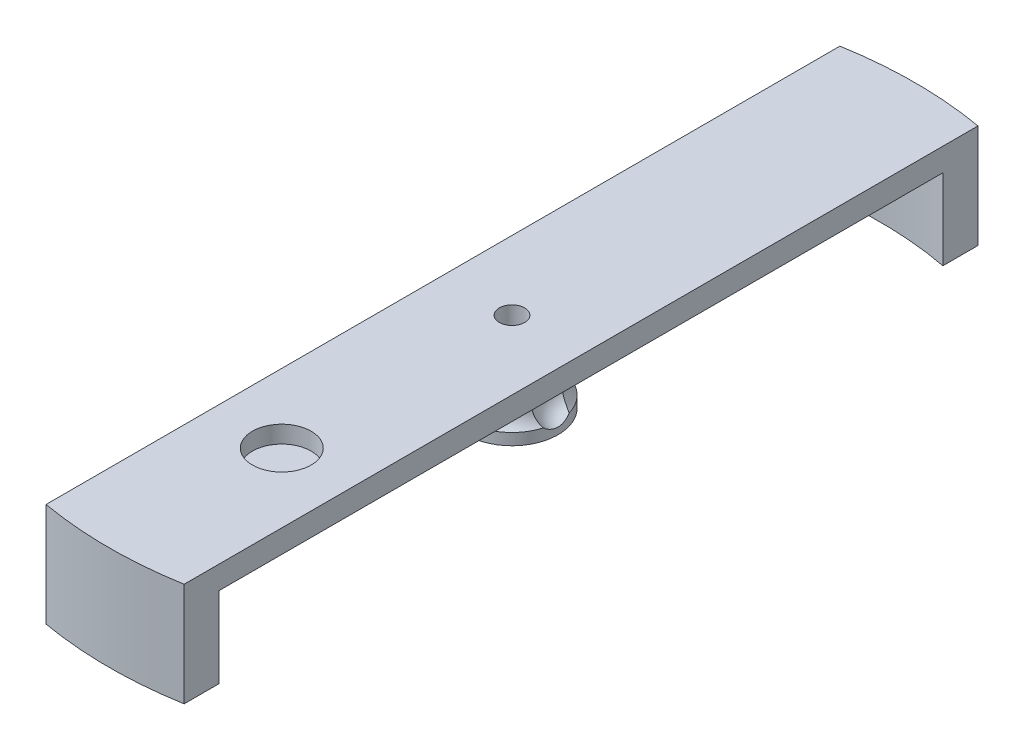
SolidWorks part; units mm, degrees
ref_plane "Plano frontal" through (0, 0, 0) normal (0, 0, 1) x (1, 0, 0)
ref_plane "Plano superior" through (0, 0, 0) normal (0, 1, 0) x (1, 0, 0)
ref_plane "Plano direito" through (0, 0, 0) normal (1, 0, 0) x (0, 0, -1)
sketch "Esboço1" plane through (0, 0, 0) normal (0, 0, 1) x (1, 0, 0)
  line L0 (0, 0) -> (0, 5.1163) construction
  line L1 (1.1, 7) -> (1.1, 0)
  line L6 (3.5, 7) -> (1.1, 7)
  line L7 (1.1, 0) -> (4, 0)
  line L8 (4, 0) -> (4, 1)
  line L9 (4, 4.0397) -> (4, 5)
  line L10 (3.5, 7) -> (35, 7)
  line L11 (35, 7) -> (35, -2)
  line L12 (35, -2) -> (32, -2)
  line L13 (32, -2) -> (32, 5)
  line L14 (32, 5) -> (4, 5)
  arc A1 (4, 4.0397) -> (4, 1) centre (5.3, 2.5199) ccw
  dimension "D3" = 0.7
  dimension "D5" = 2
  dimension "D1" = 2.2
  dimension "D2" = 8
  dimension "D4" = 7
  dimension "D6" = 1
  dimension "D7" = 2
  dimension "D8" = 2
  dimension "D9" = 3
  dimension "D10" = 70
revolve "Revolução1" add sketch "Esboço1" angle 360 about L0
sketch "Esboço2" plane through (0, 7, 0) normal (0, 1, 0) x (1, 0, 0)
  line L1 (-6, 38.1351) -> (6, 38.1351)
  line L2 (-6, 38.1351) -> (-6, -38.1351)
  line L3 (-6, -38.1351) -> (6, -38.1351)
  line L4 (6, 38.1351) -> (6, -38.1351)
  line L5 (-6, 38.1351) -> (6, -38.1351) construction
  line L6 (-6, -38.1351) -> (6, 38.1351) construction
  line L7 (-48.3706, -51.1789) -> (48.3706, -51.1789)
  line L8 (-48.3706, -51.1789) -> (-48.3706, 51.1789)
  line L9 (-48.3706, 51.1789) -> (48.3706, 51.1789)
  line L10 (48.3706, -51.1789) -> (48.3706, 51.1789)
  line L11 (-48.3706, -51.1789) -> (48.3706, 51.1789) construction
  line L12 (-48.3706, 51.1789) -> (48.3706, -51.1789) construction
  point P0 (0, 0)
  point P6 (0, 0)
  dimension "D1" = 12
extrude "Corte-extrusão1" cut sketch "Esboço2" against normal through all both and the other way through all
sketch "Esboço3" plane through (0, 0, 0) normal (0, 0, 1) x (1, 0, 0)
  line L0 (4, 5) -> (4, 0) construction
  line L2 (4, 0) -> (4, 1) construction
  line L3 (4, 4.0397) -> (4, 5) construction
  line L4 (4.5, 4.5199) -> (4.5, 0.5199)
  arc A0 (4.5, 4.5199) -> (4.5, 0.5199) centre (4.5, 2.5199) ccw
  arc A1 (4, 4.0397) -> (4, 1) centre (5.3, 2.5199) ccw construction
  point P14 (5.3, 2.5199)
  dimension "D1" = 2
  dimension "D2" = 0.8
revolve "Corte-Revolução1" cut sketch "Esboço3" angle 360 about L4
pattern_circular "PadrãoCircular1" count 4 over 360 about axis through (0, 0, 0) along (0, 1, 0) of "Corte-Revolução1"
sketch "Esboço4" plane through (0, 7, 0) normal (0, 1, 0) x (1, 0, 0)
  circle A0 centre (0, -20) radius 2.55
  circle A1 centre (0, 0) radius 1.1 construction
  point P4 (0, 0)
  dimension "D1" = 5.1
  dimension "D2" = 20
extrude "Corte-extrusão2" cut sketch "Esboço4" against normal blind 1.5
